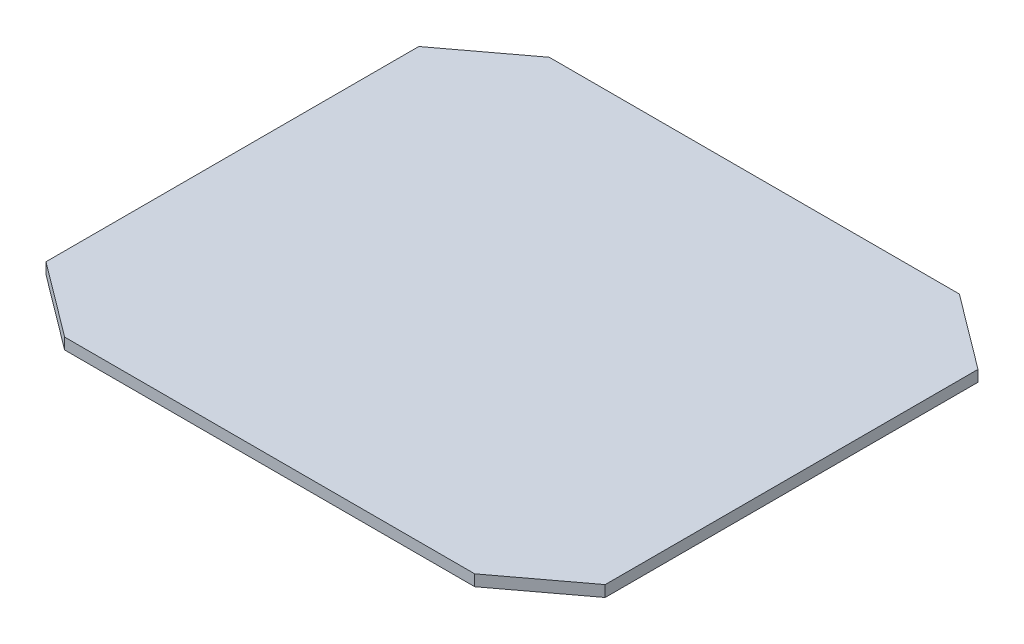
SolidWorks part; units mm, degrees
ref_plane "Front Plane" through (0, 0, 0) normal (0, 0, 1) x (1, 0, 0)
ref_plane "Top Plane" through (0, 0, 0) normal (0, 1, 0) x (1, 0, 0)
ref_plane "Right Plane" through (0, 0, 0) normal (1, 0, 0) x (0, 0, -1)
sketch "Sketch1" plane through (0, 0, 0) normal (0, 1, 0) x (1, 0, 0)
  line L1 (-75, 65) -> (75, 65)
  line L2 (-75, 65) -> (-75, -65)
  line L3 (-75, -65) -> (75, -65)
  line L4 (75, 65) -> (75, -65)
  line L5 (-75, 65) -> (75, -65) construction
  line L6 (-75, -65) -> (75, 65) construction
  point P0 (0, 0)
  dimension "D1" = 130
  dimension "D2" = 150
extrude "Boss-Extrude1" add sketch "Sketch1" along normal blind 3
sketch "Sketch2" plane through (0, 3, 0) normal (0, 1, 0) x (1, 0, 0)
  line L0 (-55, 65) -> (-75, 50)
  line L1 (75, 65) -> (-75, 65) construction
  line L2 (-75, 65) -> (-75, -65) construction
  line L3 (-75, -50) -> (-55, -65)
  line L4 (-75, -65) -> (75, -65) construction
  line L5 (75, -50) -> (55, -65)
  line L6 (75, -65) -> (75, 65) construction
  line L7 (55, 65) -> (75, 50)
  line L8 (75, -65) -> (75, -50)
  line L9 (-75, -65) -> (-55, -65)
  line L10 (-75, 65) -> (-75, 50)
  line L11 (75, 65) -> (55, 65)
  line L12 (-55, 65) -> (-75, 65)
  line L13 (-75, -50) -> (-75, -65)
  line L14 (55, -65) -> (75, -65)
  line L15 (75, 50) -> (75, 65)
  dimension "D1" = 20
  dimension "D2" = 15
extrude "Cut-Extrude1" cut sketch "Sketch2" against normal through all
